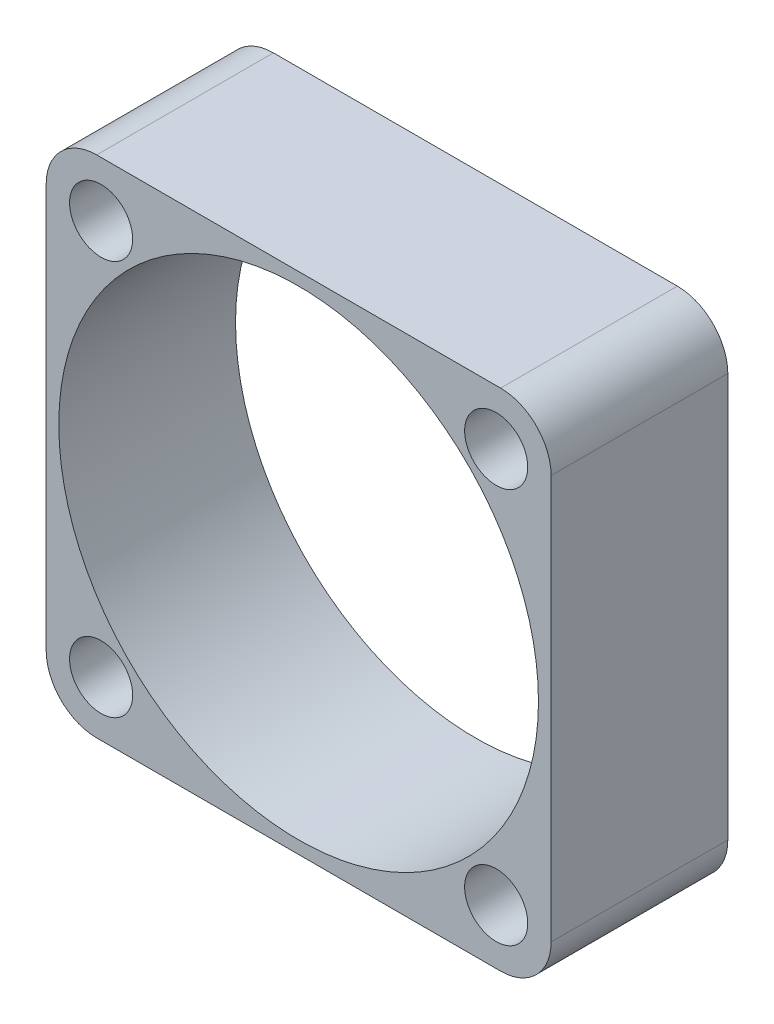
SolidWorks part; units mm, degrees
ref_plane "Front Plane" through (0, 0, 0) normal (0, 0, 1) x (1, 0, 0)
ref_plane "Top Plane" through (0, 0, 0) normal (0, 1, 0) x (1, 0, 0)
ref_plane "Right Plane" through (0, 0, 0) normal (1, 0, 0) x (0, 0, -1)
sketch "Sketch1" plane through (0, 0, 0) normal (0, 0, 1) x (1, 0, 0)
  line L1 (-10, -10) -> (10, -10)
  line L2 (-10, -10) -> (-10, 10)
  line L3 (-10, 10) -> (10, 10)
  line L4 (10, -10) -> (10, 10)
  line L5 (-10, -10) -> (10, 10) construction
  line L6 (-10, 10) -> (10, -10) construction
  circle A0 centre (0, 0) radius 9.5
  point P0 (0, 0)
  dimension "D2" = 19
  dimension "D1" = 20
extrude "Boss-Extrude1" add sketch "Sketch1" along normal blind 7
fillet "Fillet1" radius 2 4 edges at (-10, 10, 3.5) (-10, -10, 3.5) (10, -10, 3.5) (10, 10, 3.5)
sketch "Sketch2" plane through (0, 0, 7) normal (0, 0, 1) x (1, 0, 0)
  line L0 (0, 0) -> (-9.4142, 9.4142) construction
  line L1 (0, 0) -> (9.4142, 9.4142) construction
  line L2 (0, 0) -> (9.4142, -9.4142) construction
  line L3 (0, 0) -> (-9.4142, -9.4142) construction
  line L4 (-7.825, 7.825) -> (7.825, 7.825) construction
  line L5 (7.825, 7.825) -> (7.825, -7.825) construction
  line L6 (7.825, -7.825) -> (-7.825, -7.825) construction
  line L7 (-7.825, -7.825) -> (-7.825, 7.825) construction
  arc A0 (-8, 10) -> (-10, 8) centre (-8, 8) ccw construction
  arc A1 (10, 8) -> (8, 10) centre (8, 8) ccw construction
  arc A2 (8, -10) -> (10, -8) centre (8, -8) ccw construction
  arc A3 (-10, -8) -> (-8, -10) centre (-8, -8) ccw construction
  circle A4 centre (-7.825, 7.825) radius 1.25
  circle A5 centre (7.825, 7.825) radius 1.25
  circle A6 centre (7.825, -7.825) radius 1.25
  circle A7 centre (-7.825, -7.825) radius 1.25
  dimension "D1" = 2.5
  dimension "D2" = 18.15
extrude "Cut-Extrude1" cut sketch "Sketch2" against normal through all
